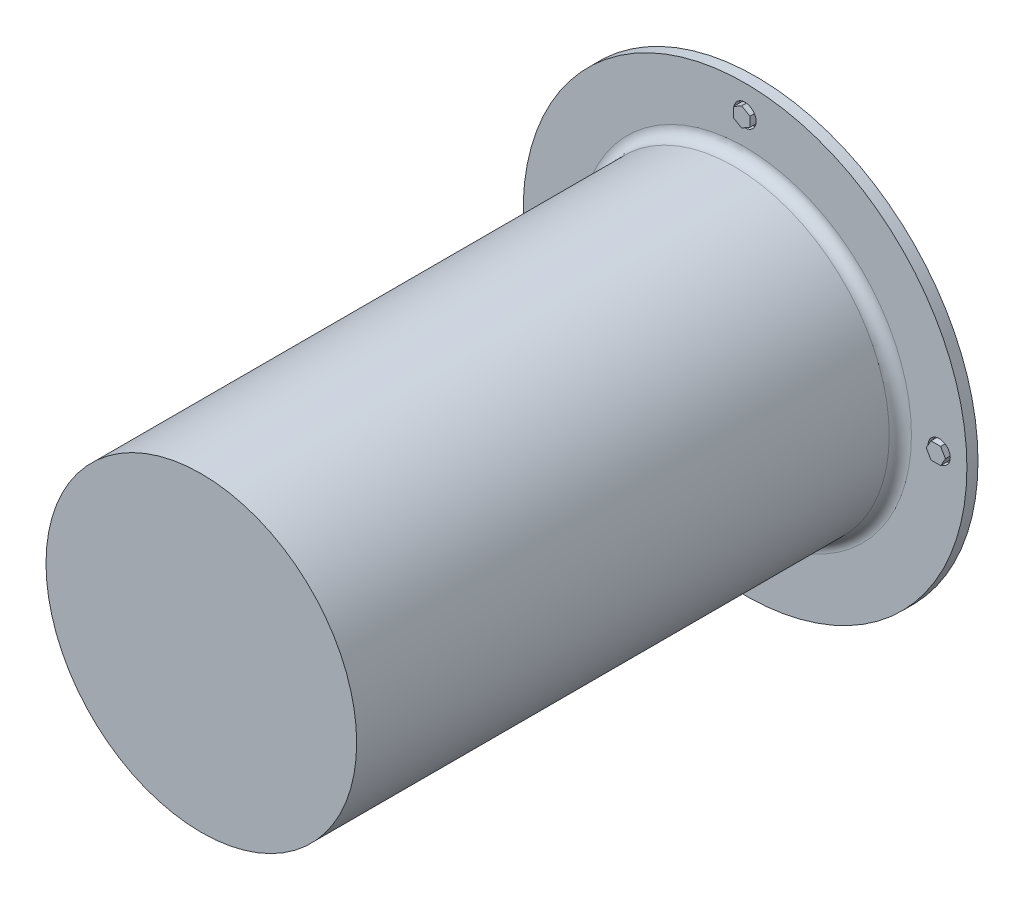
SolidWorks part; units mm, degrees
material "6061-T6 (SS)"
ref_plane "Ebene vorne" through (0, 0, 0) normal (0, 0, 1) x (1, 0, 0)
ref_plane "Ebene oben" through (0, 0, 0) normal (0, 1, 0) x (1, 0, 0)
ref_plane "Ebene rechts" through (0, 0, 0) normal (1, 0, 0) x (0, 0, -1)
sketch "Skizze1" plane through (0, 0, 0) normal (0, 0, 1) x (1, 0, 0)
  circle A0 centre (0, 0) radius 200
  dimension "D1" = 400
extrude "Aufsatz-Linear austragen1" add sketch "Skizze1" along normal blind 10
sketch "Skizze2" plane through (0, 0, 10) normal (0, 0, 1) x (1, 0, 0)
  circle A0 centre (0, 0) radius 140
  dimension "D1" = 280
extrude "Aufsatz-Linear austragen2" add sketch "Skizze2" along normal blind 490
fillet "Verrundung2" radius 10 1 edges at (140, 0, 10)
sketch "Skizze8" plane through (0, 0, 10) normal (0, 0, 1) x (1, 0, 0)
  line L0 (0, 0) -> (0, 200) construction
  circle A0 centre (0, 0) radius 200 construction
  circle A1 centre (0, 175) radius 10
  circle A2 centre (175, 0) radius 10
  circle A3 centre (0, -175) radius 10
  circle A4 centre (-175, 0) radius 10
  point P17 (0, 0)
  dimension "D1" = 20
  dimension "D2" = 25
  dimension "D3" = 4
extrude "Schnitt-Linear austragen1" cut sketch "Skizze8" against normal blind 5
sketch "Skizze9" plane through (0, 0, 5) normal (0, 0, 1) x (1, 0, 0)
  line L0 (0, 166.3397) -> (7.5, 170.6699)
  line L1 (-166.3397, 0) -> (-170.6699, 7.5)
  line L2 (-170.6699, 7.5) -> (-179.3301, 7.5)
  line L3 (-179.3301, 7.5) -> (-183.6603, 0)
  line L4 (-183.6603, 0) -> (-179.3301, -7.5)
  line L5 (-179.3301, -7.5) -> (-170.6699, -7.5)
  line L6 (-170.6699, -7.5) -> (-166.3397, 0)
  line L7 (7.5, 170.6699) -> (7.5, 179.3301)
  line L8 (7.5, 179.3301) -> (0, 183.6603)
  line L9 (0, 183.6603) -> (-7.5, 179.3301)
  line L10 (-7.5, 179.3301) -> (-7.5, 170.6699)
  line L11 (-7.5, 170.6699) -> (0, 166.3397)
  line L12 (166.3397, 0) -> (170.6699, -7.5)
  line L13 (170.6699, -7.5) -> (179.3301, -7.5)
  line L14 (179.3301, -7.5) -> (183.6603, 0)
  line L15 (183.6603, 0) -> (179.3301, 7.5)
  line L16 (179.3301, 7.5) -> (170.6699, 7.5)
  line L17 (170.6699, 7.5) -> (166.3397, 0)
  line L18 (0, -166.3397) -> (-7.5, -170.6699)
  line L19 (-7.5, -170.6699) -> (-7.5, -179.3301)
  line L20 (-7.5, -179.3301) -> (0, -183.6603)
  line L21 (0, -183.6603) -> (7.5, -179.3301)
  line L22 (7.5, -179.3301) -> (7.5, -170.6699)
  line L23 (7.5, -170.6699) -> (0, -166.3397)
  circle A0 centre (-175, 0) radius 7.5 construction
  point P30 (0, 0)
  dimension "D1" = 4
extrude "Aufsatz-Linear austragen4" add sketch "Skizze9" along normal blind 8
shell "Wandung1" thickness 15
